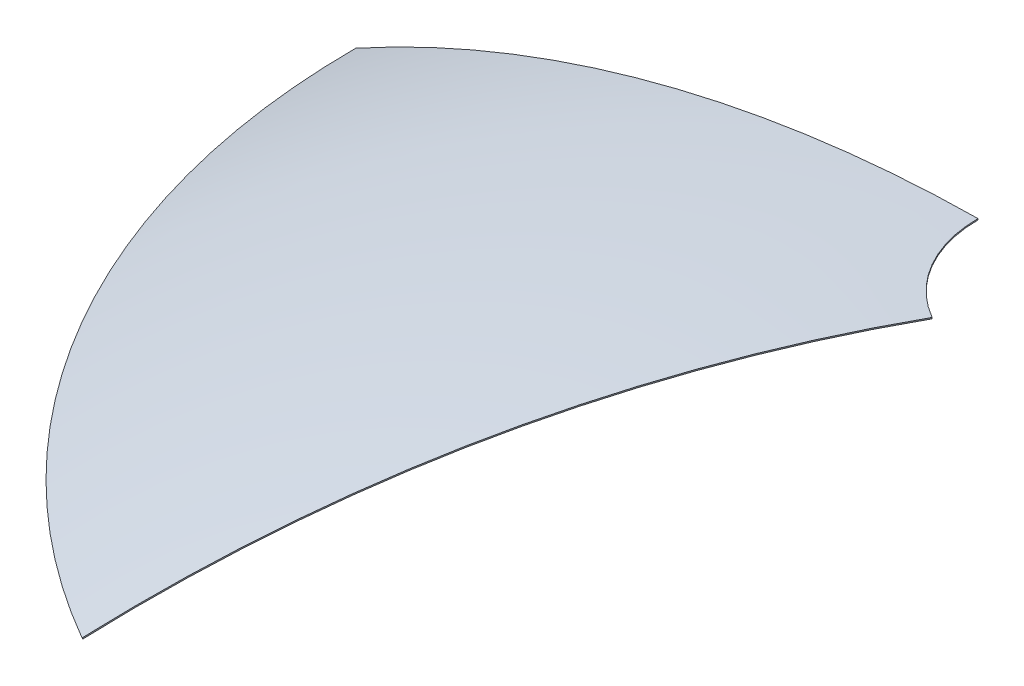
SolidWorks part; units mm, degrees
ref_plane "Front Plane" through (0, 0, 0) normal (0, 0, 1) x (1, 0, 0)
ref_plane "Top Plane" through (0, 0, 0) normal (0, 1, 0) x (1, 0, 0)
ref_plane "Right Plane" through (0, 0, 0) normal (1, 0, 0) x (0, 0, -1)
sketch "Sketch1" plane through (0, 0, 0) normal (0, 0, 1) x (1, 0, 0)
  line L0 (45, 1.9367) -> (-45, 1.9367) construction
  line L1 (45, 1.9367) -> (-45, 1.9367) construction
  line L2 (10, 1.9367) -> (-10, 1.9367) construction
  line L3 (10, 1.9367) -> (-10, 1.9367) construction
  line L4 (-45, 1.9367) -> (-10, 1.9367)
  line L6 (-45.0004, 2.4367) -> (-10, 2.4367)
  line L7 (-10, 2.4367) -> (-10, 1.9367)
  line L8 (-299.7402, -63.211) -> (-299.4992, -63.6491)
  line L9 (0, -998.5) -> (0, 49001.5) construction
  arc A1 (-46.1132, 1.9338) -> (-299.4992, -63.6491) centre (-44.2035, -527.7266) ccw
  arc A2 (-45, 1.9367) -> (-46.1132, 1.9338) centre (-44.2035, -527.7266) ccw
  arc A3 (-46.115, 2.4338) -> (-299.7402, -63.211) centre (-44.2035, -527.7266) ccw
  arc A4 (-45.0004, 2.4367) -> (-46.115, 2.4338) centre (-44.2035, -527.7266) ccw
  point P17 (0, 1.9367)
  dimension "D1" = 0.5
  dimension "D2" = 1.1132
  dimension "D3" = 264.4748
  dimension "D4" = 1.1132
  dimension "D5" = 35
revolve "Revolve1" add sketch "Sketch1" angle 60 about L9
sketch "Sketch3" plane through (0, 2.4367, 0) normal (0, 1, 0) x (1, 0, 0)
  line L0 (-10, 0) -> (-5, -8.6603)
  arc A0 (-10, 0) -> (-5, -8.6603) centre (0, 0) ccw construction
  arc A1 (-10, 0) -> (-5, -8.6603) centre (0, 0) ccw
extrude "Boss-Extrude1" [suppressed] add sketch "Sketch3" against normal up to surface (0.5 mm away)
sketch "Sketch4" plane through (0, 0, 0) normal (0, 1, 0) x (1, 0, 0)
  circle A0 centre (0, 0) radius 50.25
  dimension "D1" = 100.5
extrude "Cut-Extrude3" cut sketch "Sketch4" along normal blind 10
